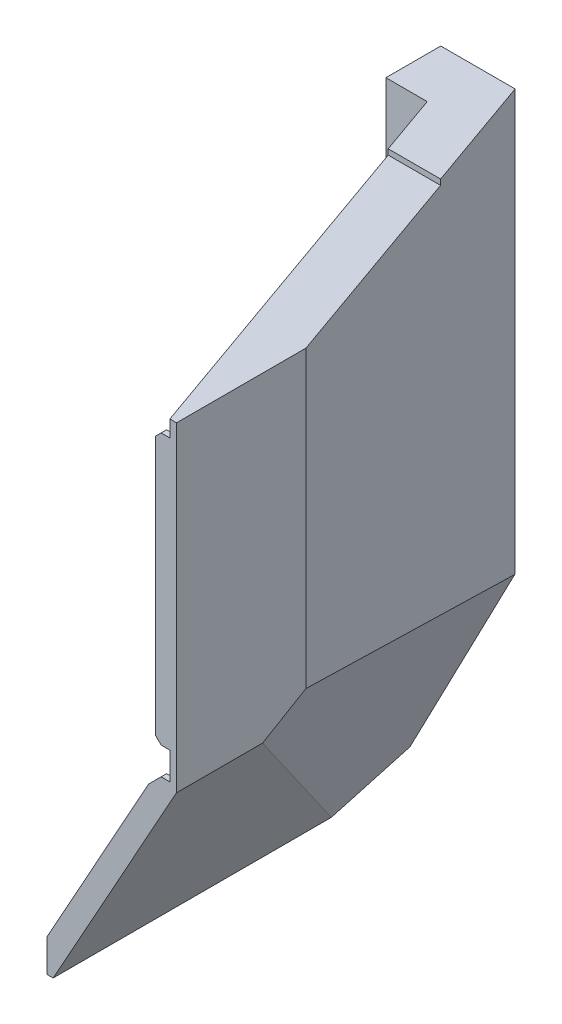
SolidWorks part; units mm, degrees
ref_plane "Plan de face" through (0, 0, 0) normal (0, 0, 1) x (1, 0, 0)
ref_plane "Plan de dessus" through (0, 0, 0) normal (0, 1, 0) x (1, 0, 0)
ref_plane "Plan de droite" through (0, 0, 0) normal (1, 0, 0) x (0, 0, -1)
sketch "Esquisse1" plane through (0, 0, 0) normal (0, 1, 0) x (1, 0, 0)
  line L0 (-258, 0) -> (-258, 609.9611) construction
  line L1 (-258, 609.9611) -> (-42.4247, 0) construction
  line L2 (-42.4247, 0) -> (-258, 0) construction
  line L3 (-42.4247, 0) -> (0, 0) construction
  line L4 (0, 0) -> (-258, 730) construction
  line L5 (-258, 609.9611) -> (-258, 730) construction
  line L6 (0, 0) -> (95.4556, 0)
  line L7 (95.4556, 0) -> (-196.1198, 825)
  line L8 (0, 0) -> (-291.5753, 825)
  line L9 (-291.5753, 825) -> (-196.1198, 825)
  line L10 (-196.1198, 825) -> (-196.1198, 0) construction
  dimension "D1" = 40
  dimension "D2" = 258
  dimension "D3" = 730
  dimension "D4" = 825
  dimension "D5" = 90
extrude "Boss.-Extru.2" add sketch "Esquisse1" along normal blind 850
sketch "Esquisse2" plane through (0, 0, -825) normal (0, 0, -1) x (-1, 0, 0)
  line L0 (196.1198, 850) -> (196.1198, 0) construction
  line L1 (196.1198, 0) -> (331.5753, 0)
  line L2 (196.1198, 0) -> (196.1198, 850)
  line L3 (196.1198, 850) -> (331.5753, 850)
  line L4 (331.5753, 0) -> (331.5753, 850)
  line L5 (196.1198, 0) -> (291.5753, 0) construction
  line L6 (196.1198, 850) -> (291.5753, 850) construction
  line L7 (291.5753, 850) -> (291.5753, 0) construction
  dimension "D1" = 40
extrude "Boss.-Extru.4" add sketch "Esquisse2" against normal blind 100
sketch "Esquisse7" plane through (-331.5753, 0, 0) normal (-1, 0, 0) x (0, 0, 1)
  line L0 (0, 850) -> (0, 0) construction
  line L1 (-615, 850) -> (0, 850)
  line L2 (-615, 850) -> (-615, 840)
  line L3 (-615, 840) -> (0, 840)
  line L4 (0, 850) -> (0, 840)
  line L5 (-725, 850) -> (0, 850) construction
  line L6 (-725, 0) -> (-725, 850) construction
  dimension "D1" = 10
  dimension "D2" = 110
extrude "Enlèv. mat.-Extru.5" cut sketch "Esquisse7" against normal through all
sketch "Esquisse8" plane through (84.8562, 0, -29.9903) normal (0.9428, 0, -0.3332) x (-0.3332, 0, -0.9428)
  line L0 (-31.8082, 280) -> (768.9475, 0)
  line L1 (-31.8082, 840) -> (-31.8082, 0) construction
  line L2 (-31.8082, 0) -> (843.201, 0) construction
  line L3 (768.9475, 0) -> (-31.8082, 0)
  line L4 (-31.8082, 0) -> (-31.8082, 280)
  dimension "D1" = 280
extrude "Enlèv. mat.-Extru.6" cut sketch "Esquisse8" against normal through all
chamfer "Chanfrein1" distance 40 angle 69 1 edges at (-37.9605, 140, -377.4951)
chamfer "Chanfrein2" distance 50 angle 60 1 edges at (-279.3754, 0, -825)
chamfer "Chanfrein3" distance 250 angle 19 1 edges at (95.4556, 615.1952, 0)
sketch "Esquisse11" plane through (0, 0, -825) normal (0, 0, -1) x (-1, 0, 0)
  line L0 (311.5753, 850) -> (311.5753, 86.6025) construction
  line L1 (196.1198, 86.6025) -> (331.5753, 86.6025) construction
  line L2 (311.5753, 86.6025) -> (216.1198, 86.6025) construction
  line L3 (216.1198, 86.6025) -> (216.1198, 850) construction
  line L4 (196.1198, 850) -> (331.5753, 850) construction
  line L5 (331.5753, 86.6025) -> (331.5753, 850) construction
  line L6 (196.1198, 850) -> (196.1198, 86.6025) construction
  line L7 (289.0753, 679.7722) -> (238.6198, 730.2278) construction
  line L8 (273.1654, 663.8623) -> (222.7099, 714.3179)
  line L9 (304.9852, 695.6821) -> (254.5297, 746.1377)
  line L10 (289.0753, 539.7722) -> (238.6198, 590.2278) construction
  line L11 (273.1654, 523.8623) -> (222.7099, 574.3179)
  line L12 (304.9852, 555.6821) -> (254.5297, 606.1377)
  line L13 (289.0753, 399.7722) -> (238.6198, 450.2278) construction
  line L14 (273.1654, 383.8623) -> (222.7099, 434.3179)
  line L15 (304.9852, 415.6821) -> (254.5297, 466.1377)
  line L16 (289.0753, 259.7722) -> (238.6198, 310.2278) construction
  line L17 (273.1654, 243.8623) -> (222.7099, 294.3179)
  line L18 (304.9852, 275.6821) -> (254.5297, 326.1377)
  line L19 (263.8476, 850) -> (263.8476, 86.6025) construction
  arc A0 (273.1654, 663.8623) -> (304.9852, 695.6821) centre (289.0753, 679.7722) ccw
  arc A1 (254.5297, 746.1377) -> (222.7099, 714.3179) centre (238.6198, 730.2278) ccw
  arc A2 (273.1654, 523.8623) -> (304.9852, 555.6821) centre (289.0753, 539.7722) ccw
  arc A3 (254.5297, 606.1377) -> (222.7099, 574.3179) centre (238.6198, 590.2278) ccw
  arc A4 (273.1654, 383.8623) -> (304.9852, 415.6821) centre (289.0753, 399.7722) ccw
  arc A5 (254.5297, 466.1377) -> (222.7099, 434.3179) centre (238.6198, 450.2278) ccw
  arc A6 (273.1654, 243.8623) -> (304.9852, 275.6821) centre (289.0753, 259.7722) ccw
  arc A7 (254.5297, 326.1377) -> (222.7099, 294.3179) centre (238.6198, 310.2278) ccw
  point P14 (263.8476, 705)
  point P23 (263.8476, 565)
  point P30 (263.8476, 425)
  point P37 (263.8476, 285)
  dimension "D1" = 20
  dimension "D2" = 20
  dimension "D3" = 45
  dimension "D4" = 45
  dimension "D5" = 145
  dimension "D7" = 140
  dimension "D6" = 4
extrude "Enlèv. mat.-Extru.9" cut sketch "Esquisse11" against normal blind 20
sketch "Esquisse12" plane through (-40.7197, 14.9785, 8.8363) normal (0.9196, -0.3383, -0.1996) x (-0.179, 0.0914, -0.9796)
  line L0 (758.2962, -87.7609) -> (129.5106, 220.361)
  line L1 (763.9526, -90.5327) -> (129.5106, 220.361) construction
  line L2 (129.5106, 220.361) -> (128.594, -274.639)
  line L3 (128.594, -274.639) -> (551.3872, -304.9904)
  line L4 (551.3872, -304.9904) -> (758.2962, -87.7609)
  line L5 (129.5106, 220.361) -> (22.2049, 258.2803) construction
  dimension "D1" = 64
  dimension "D2" = 72.5
  dimension "D3" = 495
  dimension "D4" = 94
  dimension "D5" = 300
extrude "Boss.-Extru.5" add sketch "Esquisse12" against normal blind 20
sketch "Esquisse13" plane through (0, -335.5848, -581.25) normal (0, -0.5, -0.866) x (-1, 0, 0)
  line L0 (331.5753, 387.5) -> (216.3252, 387.5)
  line L1 (331.5753, 387.5) -> (331.5753, -161.1549)
  line L2 (216.3252, 387.5) -> (195.754, 485.4301) construction
  line L3 (216.3252, 387.5) -> (331.5753, -161.1549)
extrude "Boss.-Extru.6" add sketch "Esquisse13" against normal blind 20
ref_plane "Plan1" through (-40.7197, 14.9785, 8.8363) normal (-0.9196, 0.3383, 0.1996) x (0.1873, -0.0689, 0.9799)
sketch "Esquisse14" plane through (-40.7197, 14.9785, 8.8363) normal (-0.9196, 0.3383, 0.1996) x (0.1873, -0.0689, 0.9799)
  line L0 (-558.5436, -291.6781) -> (-760.183, -69.5485)
  line L1 (-760.183, -69.5485) -> (-765.9042, -72.1839)
  line L2 (-765.9042, -72.1839) -> (-799.9273, -74.6815)
  line L3 (-799.9273, -74.6815) -> (-671.7428, -297.0794)
  line L4 (-799.9273, -74.6815) -> (-519.9684, -560.4054) construction
  line L5 (-671.7428, -297.0794) -> (-558.5436, -291.6781)
  line L6 (-135.144, -271.4758) -> (-558.5436, -291.6781) construction
extrude "Boss.-Extru.7" add sketch "Esquisse14" against normal up to surface (20 mm away)
sketch "Esquisse17" plane through (14.0599, 0, -0.114) normal (1, 0, -0.0081) x (-0.0081, 0, -1)
  line L0 (0, 268.8776) -> (0, -254.3755)
  line L1 (0, -254.3755) -> (124.8806, -230.4959)
  line L2 (124.8806, -230.4959) -> (112.7434, 233.2032)
  line L3 (112.7434, 233.2032) -> (0, 268.8776)
extrude "Boss.-Extru.8" add sketch "Esquisse17" against normal up to surface (194.5156 mm away)
sketch "Esquisse19" plane through (-27.916, 239.584, -78.9873) normal (0.11, -0.944, 0.3112) x (-0.9939, -0.1045, 0.0344)
  line L0 (-42.2331, -84.7006) -> (-41.8492, -35.1412)
  line L1 (-41.3123, 34.1614) -> (-42.2331, -84.7006) construction
  line L2 (-42.2331, -84.7006) -> (-28.0864, -84.1877)
  line L3 (-28.0864, -84.1877) -> (229.7105, 688.5453)
  line L4 (229.7105, 688.5453) -> (202.6022, 697.5891)
  line L5 (202.6022, 697.5891) -> (-41.8492, -35.1412)
  line L6 (-28.0864, -84.1877) -> (-42.2331, -84.7006) construction
  point P1 (-35.1598, -84.4442)
extrude "Boss.-Extru.14" add sketch "Esquisse19" along normal up to surface up to face at (-137.213, -20.9481, -274.708)
sketch "Esquisse20" plane through (0, 0, 0) normal (0, 1, 0) x (1, 0, 0)
  line L1 (14.0608, 0) -> (-22.7378, 0)
  line L2 (14.0608, 0) -> (14.0608, -35.8353)
  line L3 (14.0608, -35.8353) -> (-22.7378, -35.8353)
  line L4 (-22.7378, 0) -> (-22.7378, -35.8353)
extrude "Enlèv. mat.-Extru.11" cut sketch "Esquisse20" against normal through all both and the other way through all
sketch "Esquisse15" plane through (0, 0, 0) normal (0, 0, 1) x (1, 0, 0)
  line L0 (-331.5753, 86.6025) -> (-331.5753, -475.1491) construction
  line L1 (-331.5753, -190.1491) -> (14.0599, -190.1491) construction
  line L2 (-331.5753, -190.1491) -> (-331.5753, -475.1491)
  line L3 (-331.5753, -475.1491) -> (14.0599, -475.1491)
  line L4 (14.0599, -190.1491) -> (14.0599, -475.1491)
  line L6 (14.0599, 228.3016) -> (14.0599, -254.3755) construction
  line L7 (14.0599, -190.1491) -> (14.0608, 259.8509) construction
  line L8 (14.0608, 270.516) -> (14.0608, 840) construction
  line L9 (14.0608, 259.8509) -> (-235.9401, -190.1491)
  line L10 (14.0608, 259.8509) -> (14.0608, 270.516)
  line L11 (55.8469, 19.8509) -> (55.8469, -190.1491)
  line L12 (55.8469, -190.1491) -> (14.0599, -190.1491)
  line L13 (55.8469, 270.516) -> (55.8469, 19.8509)
  line L14 (-331.5753, -190.1491) -> (-235.9401, -190.1491)
  line L16 (14.0608, 270.516) -> (55.8469, 270.516)
  dimension "D1" = 285
  dimension "D2" = 450
  dimension "D3" = 250
extrude "Enlèv. mat.-Extru.10" cut sketch "Esquisse15" against normal through all both and the other way through all
sketch "Esquisse21" plane through (-99.5697, 55.3167, 0) normal (0.8742, -0.4856, 0) x (0, 0, -1)
  line L0 (321.4247, -305.5422) -> (543.0684, -280.803)
  line L1 (543.0684, -280.803) -> (155.7737, 231.3776)
  line L2 (155.7737, 231.3776) -> (0, 233.979)
  line L3 (0, 233.979) -> (0, 205.026)
  line L4 (0, 205.026) -> (0, -305.5422)
  line L5 (0, -305.5422) -> (321.4247, -305.5422)
extrude "Boss.-Extru.15" add sketch "Esquisse21" against normal blind 10
sketch "Esquisse23" plane through (0, 0, 0) normal (0, 0, 1) x (1, 0, 0)
  line L0 (-331.5753, -190.1491) -> (-331.5753, -260.8164)
  line L1 (-331.5753, -190.1491) -> (-102.0825, -190.1491) construction
  line L2 (-331.5753, -190.1491) -> (-331.5753, -148.1491)
  line L3 (-331.5753, -148.1491) -> (-102.0825, -148.1491)
  line L4 (-102.0825, -190.1491) -> (-102.0825, -148.1491)
  line L5 (-331.5753, -260.8164) -> (-102.0825, -260.8164)
  line L6 (-102.0825, -190.1491) -> (-102.0825, -260.8164)
  point P0 (-331.5753, -190.1491)
  dimension "D1" = 42
extrude "Enlèv. mat.-Extru.12" cut sketch "Esquisse23" against normal through all
sketch "Esquisse26" plane through (0, 0, 0) normal (0, 0, 1) x (1, 0, 0)
  line L0 (-224.0463, -148.1491) -> (-224.0463, 810) construction
  line L1 (-224.0463, 810) -> (14.0608, 810) construction
  line L2 (14.0608, 270.516) -> (14.0608, 840) construction
  line L3 (14.0608, 810) -> (14.0608, 317.5769)
  line L4 (14.0608, 317.5769) -> (-25.9392, 317.5769)
  line L5 (-25.9392, 317.5769) -> (-25.9392, 267.5769) construction
  line L6 (-25.9392, 267.5769) -> (14.0608, 267.5769)
  line L7 (14.0608, 267.5769) -> (12.7975, 257.5769)
  line L8 (12.7975, 257.5769) -> (-212.6067, -148.1491)
  line L9 (-212.6067, -148.1491) -> (-224.0463, -148.1491)
  line L10 (0, 840) -> (-217.3562, 840) construction
  line L13 (-25.9392, 267.5769) -> (-224.0463, -89.0145)
  line L14 (-224.0463, -89.0145) -> (-224.0463, -148.1491)
  line L15 (-25.9392, 810) -> (14.0608, 810) construction
  line L16 (0, 255.1327) -> (-224.0463, -148.1491) construction
  line L17 (14.0608, 810) -> (14.0608, 840)
  line L18 (14.0608, 840) -> (0, 840)
  line L19 (0, 840) -> (0, 810)
  line L20 (0, 810) -> (-25.9392, 810)
  line L22 (-25.9392, 810) -> (-25.9392, 317.5769)
  dimension "D1" = 30
  dimension "D2" = 50
  dimension "D3" = 10
  dimension "D4" = 40
extrude "Boss.-Extru.17" add sketch "Esquisse26" against normal blind 10
sketch "Esquisse24" plane through (14.0599, 0, -0.114) normal (1, 0, -0.0081) x (-0.0081, 0, -1)
  line L0 (-0.114, 259.8509) -> (155.6647, 257.5769)
  line L1 (155.6647, 257.5769) -> (33.6338, 259.3583) construction
  line L2 (-0.114, 259.8509) -> (-0.114, 840)
  line L3 (-0.114, 840) -> (235.6055, 840)
  line L5 (235.6055, 840) -> (235.6055, 302.9729)
  line L6 (235.6055, 302.9729) -> (155.6647, 257.5769)
extrude "Enlèv. mat.-Extru.13" cut sketch "Esquisse24" along normal blind 10
chamfer "Chanfrein6" distance 10 angle 45 3 edges at (-25.9392, 810, -5) (-25.9392, 267.5769, -5) (-25.9392, 317.5769, -5)
sketch "Esquisse9" plane through (0, -335.5848, -581.25) normal (0, -0.5, -0.866) x (-1, 0, 0)
  line L4 (311.5753, 438.3869) -> (226.0724, 438.3869)
  line L5 (226.0724, 438.3869) -> (236.5753, 388.3869)
  line L6 (236.5753, 388.3869) -> (311.5753, 388.3869)
  line L7 (311.5753, 388.3869) -> (311.5753, 438.3869)
  line L8 (219.9569, 467.5) -> (268.4949, 236.4322)
  line L9 (268.4949, 236.4322) -> (311.5753, 236.4322)
  line L10 (311.5753, 236.4322) -> (311.5753, 467.5)
  line L11 (311.5753, 467.5) -> (219.9569, 467.5)
  line L12 (219.9569, 467.5) -> (268.4949, 236.4322) construction
  line L13 (268.4949, 236.4322) -> (311.5753, 236.4322) construction
  line L14 (311.5753, 236.4322) -> (311.5753, 467.5) construction
  line L15 (311.5753, 467.5) -> (219.9569, 467.5) construction
  line L16 (236.5753, 388.3869) -> (236.5753, 438.3869) construction
  line L17 (311.5753, 343.1758) -> (246.0724, 343.1758)
  line L18 (246.0724, 343.1758) -> (256.5753, 293.1758)
  line L19 (256.5753, 293.1758) -> (311.5753, 293.1758)
  line L20 (311.5753, 293.1758) -> (311.5753, 343.1758)
  dimension "D2" = 50
  dimension "D3" = 75
  dimension "D4" = 50
  dimension "D5" = 55
  dimension "D1" = 20
extrude "Enlèv. mat.-Extru.7" cut sketch "Esquisse9" against normal blind 20
sketch "Esquisse28" plane through (0, 0, 0) normal (0, 1, 0) x (1, 0, 0)
  line L1 (12.1492, 235.7118) -> (62.2561, 235.7118)
  line L2 (12.1492, 235.7118) -> (12.1492, 0)
  line L3 (12.1492, 0) -> (62.2561, 0)
  line L4 (62.2561, 235.7118) -> (62.2561, 0)
extrude "Enlèv. mat.-Extru.15" cut sketch "Esquisse28" along normal through all
